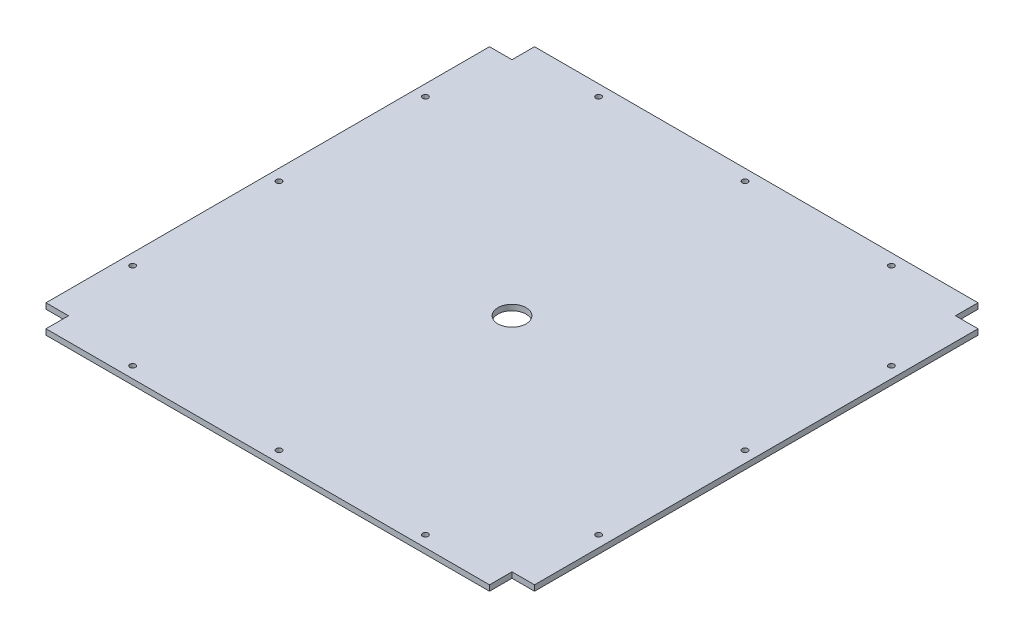
SolidWorks part; units mm, degrees
ref_plane "Front Plane" through (0, 0, 0) normal (0, 0, 1) x (1, 0, 0)
ref_plane "Top Plane" through (0, 0, 0) normal (0, 1, 0) x (1, 0, 0)
ref_plane "Right Plane" through (0, 0, 0) normal (1, 0, 0) x (0, 0, -1)
sketch "Sketch1" plane through (0, 0, 0) normal (0, 1, 0) x (1, 0, 0)
  line L1 (-217, 217) -> (217, 217)
  line L2 (-217, 217) -> (-217, -217)
  line L3 (-217, -217) -> (217, -217)
  line L4 (217, 217) -> (217, -217)
  line L5 (-217, 217) -> (217, -217) construction
  line L6 (-217, -217) -> (217, 217) construction
  point P0 (0, 0)
extrude "Boss-Extrude1" add sketch "Sketch1" along normal blind 5
sketch "Sketch2" plane through (0, 5, 0) normal (0, 1, 0) x (1, 0, 0)
  line L0 (0, 0) -> (0, 76.6055)
  line L1 (0, 0) -> (47.7215, 0)
  line L2 (-217, 217) -> (-207, 217)
  line L3 (217, 217) -> (-217, 217) construction
  line L4 (0, 0) -> (76.6055, 0)
  line L6 (0, 0) -> (0, -47.7215)
  line L7 (0, 0) -> (0, -76.6055)
  line L8 (0, 0) -> (-47.7215, 0)
  line L9 (0, 0) -> (-76.6055, 0)
  line L10 (0, 0) -> (0, 47.7215)
  circle A0 centre (-207, 130) radius 2.5
  circle A1 centre (-207, 0) radius 2.5
  circle A2 centre (-207, -130) radius 2.5
  circle A3 centre (207, -130) radius 2.5
  circle A4 centre (207, 0) radius 2.5
  circle A5 centre (207, 130) radius 2.5
  circle A6 centre (130, 207) radius 2.5
  circle A7 centre (0, 207) radius 2.5
  circle A8 centre (-130, 207) radius 2.5
  circle A9 centre (-130, -207) radius 2.5
  circle A10 centre (0, -207) radius 2.5
  circle A11 centre (130, -207) radius 2.5
  circle A12 centre (207, -130) radius 2.5
  circle A13 centre (207, 0) radius 2.5
  circle A14 centre (207, 130) radius 2.5
  circle A15 centre (-207, 130) radius 2.5
  circle A16 centre (-207, 0) radius 2.5
  circle A17 centre (-207, -130) radius 2.5
  circle A18 centre (-130, -207) radius 2.5
  circle A19 centre (0, -207) radius 2.5
  circle A20 centre (130, -207) radius 2.5
  circle A21 centre (130, 207) radius 2.5
  circle A22 centre (0, 207) radius 2.5
  circle A23 centre (-130, 207) radius 2.5
  point P66 (0, 0)
  dimension "D1" = 4
extrude "Cut-Extrude1" cut sketch "Sketch2" against normal blind 5 contours A2 | A9 | A10 | A11 | A3 | A4 | A5 | A6 | A7 | A8 | A0 | A1
sketch "Sketch3" plane through (0, 5, 0) normal (0, 1, 0) x (1, 0, 0)
  circle A0 centre (0, 0) radius 12.5
extrude "Cut-Extrude2" cut sketch "Sketch3" against normal blind 5
sketch "Sketch4" plane through (0, 5, 0) normal (0, 1, 0) x (1, 0, 0)
  line L0 (0, 0) -> (0, 12.5)
  line L1 (-217, 217) -> (-197, 217)
  line L2 (-217, 217) -> (-217, 197)
  line L3 (-217, 197) -> (-197, 197)
  line L4 (-197, 217) -> (-197, 197)
  line L5 (217, 217) -> (217, 197)
  line L6 (217, 217) -> (197, 217)
  line L7 (197, 217) -> (197, 197)
  line L8 (217, 197) -> (197, 197)
  line L9 (217, -217) -> (197, -217)
  line L10 (217, -217) -> (217, -197)
  line L11 (217, -197) -> (197, -197)
  line L12 (197, -217) -> (197, -197)
  line L13 (-217, -217) -> (-217, -197)
  line L14 (-217, -217) -> (-197, -217)
  line L15 (-197, -217) -> (-197, -197)
  line L16 (-217, -197) -> (-197, -197)
  circle A0 centre (0, 0) radius 12.5 construction
  point P26 (0, 0)
  line M12 (217, -217) -> (217, 217)
  line M13 (217, 217) -> (-217, 217)
  line M14 (-217, 217) -> (-217, -217)
  line M15 (-217, -217) -> (217, -217)
  dimension "D1" = 4
extrude "Cut-Extrude3" cut sketch "Sketch4" against normal blind 10 contours L4 L3 M13 M14 | L8 L7 M12 M13 | L12 L11 M15 M12 | L16 L15 M14 M15
